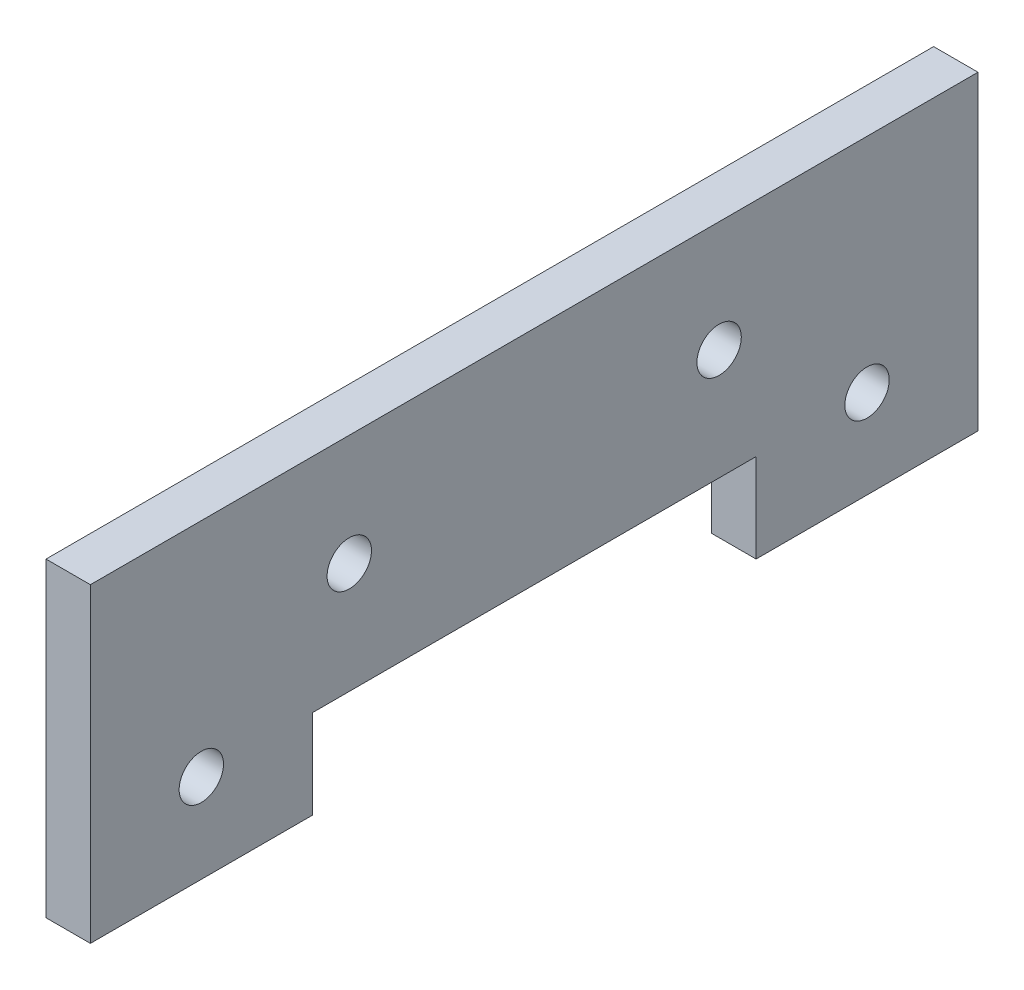
SolidWorks part; units mm, degrees
ref_plane "前视基准面" through (0, 0, 0) normal (0, 0, 1) x (1, 0, 0)
ref_plane "上视基准面" through (0, 0, 0) normal (0, 1, 0) x (1, 0, 0)
ref_plane "右视基准面" through (0, 0, 0) normal (1, 0, 0) x (0, 0, -1)
sketch "草图1" plane through (0, 0, 0) normal (1, 0, 0) x (0, 0, -1)
  line L0 (0, 0) -> (60, 0)
  line L1 (60, 0) -> (60, -21)
  line L2 (60, -21) -> (45, -21)
  line L3 (45, -21) -> (45, -15)
  line L4 (45, -15) -> (15, -15)
  line L5 (15, -15) -> (15, -21)
  line L6 (15, -21) -> (0, -21)
  line L7 (0, -21) -> (0, 0)
  dimension "D1" = 15
  dimension "D2" = 15
  dimension "D3" = 21
  dimension "D4" = 15
  dimension "D5" = 21
  dimension "D6" = 60
extrude "凸台-拉伸1" add sketch "草图1" along normal blind 3
sketch "草图2" plane through (3, 0, 0) normal (1, 0, 0) x (0, 0, -1)
  line L0 (60, 0) -> (0, 0) construction
  line L1 (0, -21) -> (15, -21) construction
  line L2 (45, -21) -> (60, -21) construction
  circle A0 centre (42.5, -7.5) radius 1.5
  circle A1 centre (17.5, -7.5) radius 1.5
  circle A2 centre (52.5, -15) radius 1.5
  circle A3 centre (7.5, -15) radius 1.5
  point P10 (0, 0)
  point P11 (0, 0)
  point P14 (7.5, -21)
  point P15 (0, 0)
  point P18 (52.5, -21)
  dimension "D1" = 3
  dimension "D2" = 7.5
  dimension "D3" = 6
  dimension "D4" = 6
  dimension "D5" = 10
  dimension "D6" = 10
extrude "切除-拉伸1" cut sketch "草图2" against normal blind 3
